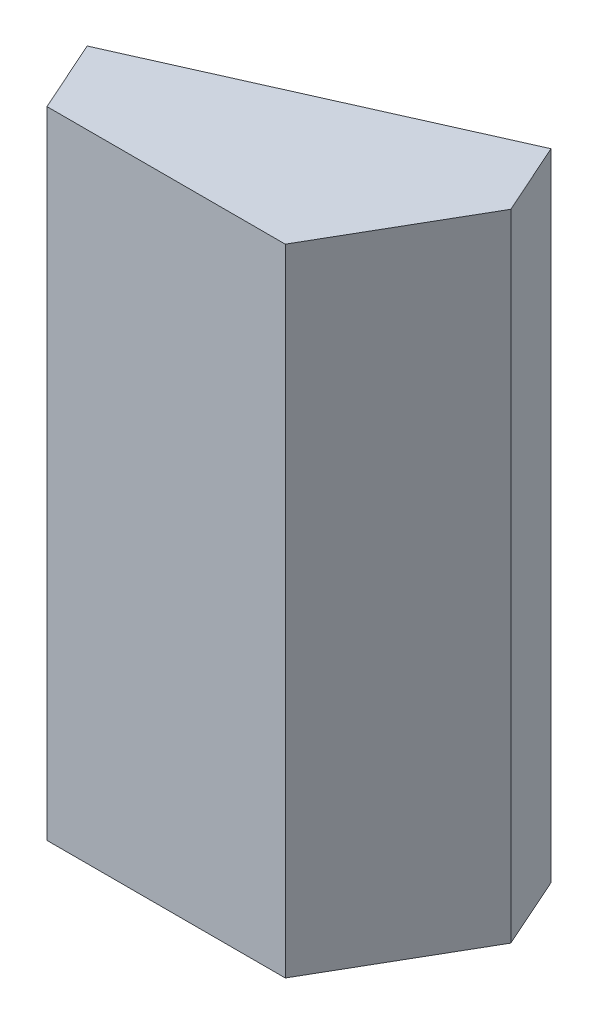
SolidWorks part; units mm, degrees
material "Pure Lead"
ref_plane "Front Plane" through (0, 0, 0) normal (0, 0, 1) x (1, 0, 0)
ref_plane "Top Plane" through (0, 0, 0) normal (0, 1, 0) x (1, 0, 0)
ref_plane "Right Plane" through (0, 0, 0) normal (1, 0, 0) x (0, 0, -1)
sketch "Sketch1" plane through (0, 0, 0) normal (0, 1, 0) x (1, 0, 0)
  line L0 (-19.05, 0) -> (0, 0)
  line L5 (0, 0) -> (6.5991, 11.43)
  line L7 (-19.05, 0) -> (-21.6347, 5.8001)
  line L8 (-21.6347, 5.8001) -> (4.0144, 17.2301)
  line L9 (4.0144, 17.2301) -> (6.5991, 11.43)
  line L10 (6.5991, 11.43) -> (-19.05, 0) construction
  point P2 (5.3079, 19.9207)
  dimension "D1" = 120
  dimension "D2" = 19.05
  dimension "D3" = 6.35
  dimension "D4" = 11.43
extrude "Boss-Extrude1" add sketch "Sketch1" along normal blind 50.8
